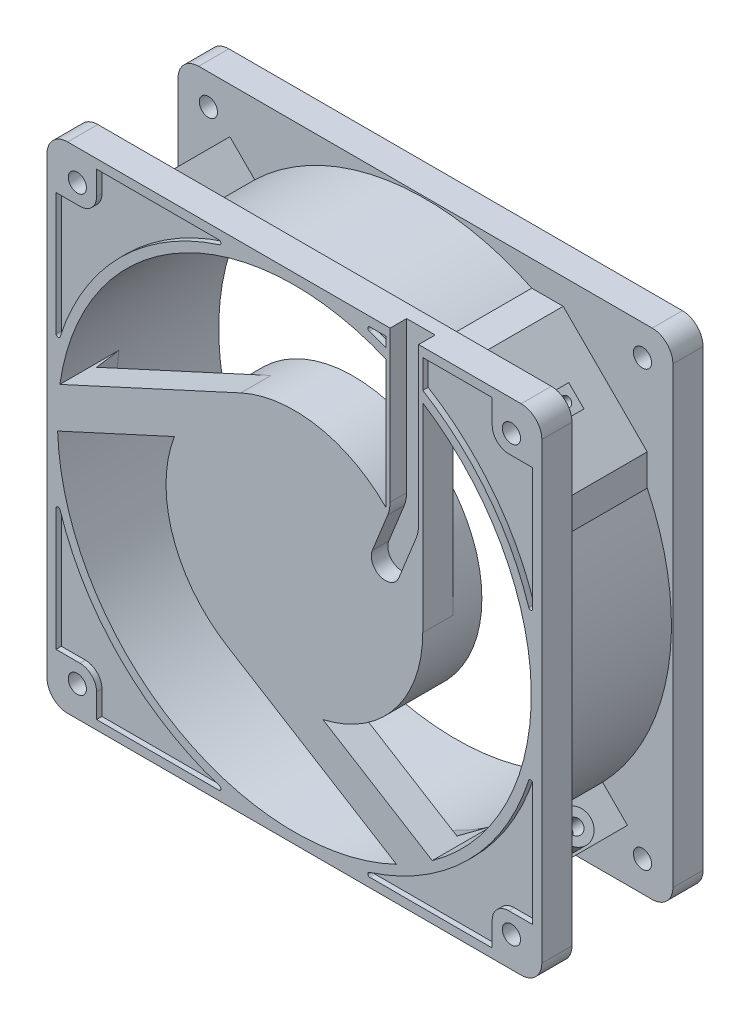
SolidWorks part; units mm, degrees
ref_plane "Plane1" through (0, 0, 0) normal (0, 0, 1) x (1, 0, 0)
ref_plane "Plane2" through (0, 0, 0) normal (0, 1, 0) x (1, 0, 0)
ref_plane "Plane3" through (0, 0, 0) normal (1, 0, 0) x (0, 0, -1)
sketch "Sketch1" plane through (0, 0, 0) normal (0, 0, 1) x (1, 0, 0)
  line L1 (-54.85, 59.85) -> (54.85, 59.85)
  line L2 (-59.85, 54.85) -> (-59.85, -54.85)
  line L3 (-54.85, -59.85) -> (54.85, -59.85)
  line L4 (59.85, 54.85) -> (59.85, -54.85)
  circle A0 centre (-52.5, 52.5) radius 2.2
  circle A1 centre (52.5, 52.5) radius 2.2
  circle A2 centre (52.5, -52.5) radius 2.2
  circle A3 centre (-52.5, -52.5) radius 2.2
  circle A4 centre (0, 0) radius 57.3
  arc A5 (59.85, 54.85) -> (54.85, 59.85) centre (54.85, 54.85) ccw
  arc A6 (59.85, -54.85) -> (54.85, -59.85) centre (54.85, -54.85) cw
  arc A7 (-54.85, -59.85) -> (-59.85, -54.85) centre (-54.85, -54.85) cw
  arc A8 (-59.85, 54.85) -> (-54.85, 59.85) centre (-54.85, 54.85) cw
  dimension "D3" = 4.4
  dimension "D5" = 114.6
  dimension "D6" = 5
  dimension "D11" = 105
  dimension "D1" = 119.7
  dimension "D2" = 119.7
  dimension "D4" = 7.35
  dimension "D7" = 59.85
  dimension "D8" = 59.85
  dimension "D9" = 105
  dimension "D10" = 7.35
extrude "Base-Extrude" add sketch "Sketch1" along normal mid plane 39
sketch "Sketch2" plane through (0, 0, 19.5) normal (0, 0, 1) x (1, 0, 0)
  line L34 (-18.2723, 57.65) -> (-47.85, 57.65)
  line L35 (57.65, 18.2723) -> (57.65, 47.85)
  line L36 (18.2723, -57.65) -> (47.85, -57.65)
  line L37 (-57.65, -18.2723) -> (-57.65, -47.85)
  line L38 (-57.65, 54.85) -> (-57.65, -54.85)
  line L39 (54.85, 57.65) -> (-54.85, 57.65)
  line L40 (57.65, -54.85) -> (57.65, 54.85)
  line L41 (-54.85, -57.65) -> (54.85, -57.65)
  line L42 (-57.65, 47.85) -> (-57.65, 18.2723)
  line L43 (47.85, 57.65) -> (18.2723, 57.65)
  line L44 (57.65, -47.85) -> (57.65, -18.2723)
  line L45 (-47.85, -57.65) -> (-18.2723, -57.65)
  line L55 (47.85, 57.65) -> (47.85, 51.85)
  line L56 (51.85, 47.85) -> (57.65, 47.85)
  line L57 (51.85, -47.85) -> (57.65, -47.85)
  line L58 (47.85, -51.85) -> (47.85, -57.65)
  line L59 (-57.65, -47.85) -> (-51.85, -47.85)
  line L60 (-47.85, -51.85) -> (-47.85, -57.65)
  line L61 (-57.65, 47.85) -> (-51.85, 47.85)
  line L62 (-47.85, 51.85) -> (-47.85, 57.65)
  arc A10 (47.85, -51.85) -> (51.85, -47.85) centre (51.85, -51.85) cw
  arc A11 (51.85, 47.85) -> (47.85, 51.85) centre (51.85, 51.85) cw
  arc A12 (-47.85, 51.85) -> (-51.85, 47.85) centre (-51.85, 51.85) cw
  arc A13 (-47.85, -51.85) -> (-51.85, -47.85) centre (-51.85, -51.85) ccw
  arc A14 (-18.2723, -57.65) -> (-18.12, -56.6737) centre (-18.2723, -57.15) ccw
  arc A15 (-57.65, -18.2723) -> (-56.6738, -18.12) centre (-57.15, -18.2723) cw
  arc A16 (18.2723, -57.65) -> (18.12, -56.6737) centre (18.2723, -57.15) cw
  arc A17 (56.6737, 18.12) -> (18.12, 56.6737) centre (0, 0) ccw
  circle A18 centre (0, 0) radius 59.5
  arc A19 (-18.12, 56.6737) -> (-56.6738, 18.12) centre (0, 0) ccw
  arc A20 (-57.65, -54.85) -> (-54.85, -57.65) centre (-54.85, -54.85) ccw
  arc A21 (-54.85, 57.65) -> (-57.65, 54.85) centre (-54.85, 54.85) ccw
  arc A22 (57.65, 54.85) -> (54.85, 57.65) centre (54.85, 54.85) ccw
  arc A23 (54.85, -57.65) -> (57.65, -54.85) centre (54.85, -54.85) ccw
  arc A24 (57.65, -18.2723) -> (56.6737, -18.12) centre (57.15, -18.2723) ccw
  arc A25 (57.65, 18.2723) -> (56.6737, 18.12) centre (57.15, 18.2723) cw
  arc A26 (18.2723, 57.65) -> (18.12, 56.6737) centre (18.2723, 57.15) ccw
  arc A27 (-18.2723, 57.65) -> (-18.12, 56.6737) centre (-18.2723, 57.15) cw
  arc A28 (18.12, -56.6737) -> (56.6737, -18.12) centre (0, 0) ccw
  arc A29 (-56.6738, -18.12) -> (-18.12, -56.6737) centre (0, 0) ccw
  arc A30 (-57.65, 18.2723) -> (-56.6738, 18.12) centre (-57.15, 18.2723) ccw
  point P54 (-57.65, -14.7217)
  point P57 (14.7217, -57.65)
  point P62 (57.65, 14.7217)
  point P67 (-14.7217, 57.65)
  dimension "D7" = 4
  dimension "D8" = 0.5
  dimension "D3" = 47.85
  dimension "D5" = 47.85
  dimension "D9" = 47.85
  dimension "D10" = 4
  dimension "D4" = 51.85
  dimension "D6" = 47.85
  dimension "D12" = 47.85
  dimension "D13" = 4
  dimension "D11" = 47.85
  dimension "D1" = 2.2
  dimension "D2" = 2.2
extrude "Cut-Extrude2" cut sketch "Sketch2" against normal blind 1.3
mirror "Mirror1" about plane through (0, 0, 0) normal (0, 0, 1) of "Cut-Extrude2"
sketch "Sketch3" plane through (0, 0, 0) normal (0, 0, 1) x (1, 0, 0)
  line L0 (-48.8611, 47.3054) -> (-47.3054, 48.8611)
  line L2 (54.85, 59.85) -> (-54.85, 59.85) construction
  line L3 (47.3054, -48.8611) -> (48.8611, -47.3054)
  line L4 (42.8435, -41.2878) -> (48.8611, -47.3054)
  line L5 (-48.8611, 47.3054) -> (-42.8435, 41.2878)
  line L6 (-48.8611, -47.3054) -> (-47.3054, -48.8611)
  line L7 (-47.3054, 48.8611) -> (-41.2878, 42.8435)
  line L8 (-48.8611, -47.3054) -> (-42.8435, -41.2878)
  line L9 (-47.3054, -48.8611) -> (-41.2878, -42.8435)
  line L10 (41.2878, -42.8435) -> (47.3054, -48.8611)
  line L11 (-59.85, 54.85) -> (-59.85, -54.85) construction
  line L12 (-54.85, -59.85) -> (54.85, -59.85) construction
  line L14 (33.3241, 53.65) -> (53.65, 33.3241)
  line L17 (47.85, 53.65) -> (18.2723, 53.65)
  line L18 (33.3241, 53.65) -> (25.728, 53.65)
  line L19 (59.85, -54.85) -> (59.85, 54.85) construction
  line L20 (53.65, 18.2723) -> (53.65, 47.85)
  line L21 (53.65, 25.728) -> (53.65, 33.3241)
  line L22 (-59.85, 54.85) -> (-59.85, -54.85)
  line L23 (-54.85, -59.85) -> (54.85, -59.85)
  line L24 (59.85, -54.85) -> (59.85, 54.85)
  line L25 (54.85, 59.85) -> (-54.85, 59.85)
  arc A0 (56.6737, 18.12) -> (18.12, 56.6737) centre (0, 0) ccw construction
  arc A1 (56.6737, -18.12) -> (53.65, 25.728) centre (0, 0) ccw
  arc A2 (18.12, -56.6737) -> (56.6737, -18.12) centre (0, 0) ccw construction
  arc A3 (-41.2878, -42.8435) -> (18.12, -56.6737) centre (0, 0) ccw
  arc A4 (-42.8435, 41.2878) -> (-42.8435, -41.2878) centre (0, 0) ccw
  arc A5 (18.12, -56.6737) -> (41.2878, -42.8435) centre (0, 0) ccw
  arc A6 (42.8435, -41.2878) -> (56.6737, -18.12) centre (0, 0) ccw
  arc A7 (25.728, 53.65) -> (-41.2878, 42.8435) centre (0, 0) ccw
  arc A9 (-59.85, -54.85) -> (-54.85, -59.85) centre (-54.85, -54.85) ccw construction
  arc A10 (54.85, -59.85) -> (59.85, -54.85) centre (54.85, -54.85) ccw construction
  arc A12 (59.85, 54.85) -> (54.85, 59.85) centre (54.85, 54.85) ccw construction
  arc A13 (-59.85, -54.85) -> (-54.85, -59.85) centre (-54.85, -54.85) ccw
  arc A14 (54.85, -59.85) -> (59.85, -54.85) centre (54.85, -54.85) ccw
  arc A15 (59.85, 54.85) -> (54.85, 59.85) centre (54.85, 54.85) ccw
  arc A16 (-54.85, 59.85) -> (-59.85, 54.85) centre (-54.85, 54.85) ccw construction
  arc A17 (-54.85, 59.85) -> (-59.85, 54.85) centre (-54.85, 54.85) ccw
  dimension "D1" = 10.9889
  dimension "D7" = 12.5446
  dimension "D6" = 1.5556
  dimension "D2" = 12.5446
  dimension "D3" = 12.5446
  dimension "D4" = 10.9889
  dimension "D5" = 107.1554
  dimension "D8" = 10.9889
  dimension "D9" = 107.1554
  dimension "D10" = 1.5556
  dimension "D11" = 12.5446
  dimension "D12" = 1.1
  dimension "D13" = 1.1
  dimension "D14" = 2.2
  dimension "D15" = 61.5
  dimension "D16" = 4
  dimension "D17" = 4
extrude "Cut-Extrude3" cut sketch "Sketch3" against normal mid plane 24.4
sketch "Sketch4" plane through (62.5613, 24.4129, 0) normal (-0.7071, -0.7071, 0) x (0.7071, -0.7071, 0)
  line L1 (-24.375, 2.6) -> (-29.575, 2.6)
  line L2 (-24.375, 2.6) -> (-24.375, -2.6)
  line L3 (-24.375, -2.6) -> (-29.575, -2.6)
  line L4 (-29.575, 2.6) -> (-29.575, -2.6)
  circle A0 centre (-26.975, 0) radius 1.2
  dimension "D5" = 2.4
  dimension "D1" = 5.2
  dimension "D2" = 5.2
  dimension "D3" = 2.6
  dimension "D4" = 2.6
extrude "Boss-Extrude2" add sketch "Sketch4" against normal blind 3.7
sketch "Sketch5" plane through (0.7778, 0.7778, 0) normal (0.7071, 0.7071, 0) x (-0.7071, 0.7071, 0)
  line L0 (-59.4898, -12.2) -> (-59.4898, 12.2) construction
  circle A0 centre (-63.7398, 0) radius 3.7
  circle A1 centre (-63.7398, 0) radius 1.7
  dimension "D1" = 7.4
  dimension "D3" = 3.4
  dimension "D2" = 4.25
extrude "Boss-Extrude3" add sketch "Sketch5" along normal blind 3.7
sketch "Sketch6" plane through (0, 0, 19.5) normal (0, 0, 1) x (1, 0, 0)
  line L0 (31.05, 59.85) -> (31.05, 0)
  line L1 (22.15, 59.85) -> (22.15, 21.7596)
  line L2 (54.85, 59.85) -> (-54.85, 59.85) construction
  line L3 (31.05, 59.85) -> (22.15, 59.85)
  line L4 (6.8925, -30.2753) -> (33.3508, -46.5941)
  line L5 (-12.9578, 28.217) -> (-56.7218, 8.1197)
  line L6 (-29.0179, 11.0483) -> (-57.2677, -1.9246)
  line L7 (-16.2999, -26.4276) -> (24.6888, -51.7083)
  line L8 (-18.2723, 57.65) -> (-47.85, 57.65) construction
  line L9 (-54.85, -59.85) -> (54.85, -59.85) construction
  arc A0 (22.15, 21.7596) -> (-12.9578, 28.217) centre (0, 0) ccw
  circle A1 centre (0, 0) radius 57.3 construction
  arc A2 (-56.7218, 8.1197) -> (-57.2677, -1.9246) centre (0, 0) ccw
  arc A3 (-29.0179, 11.0483) -> (-16.2999, -26.4276) centre (0, 0) ccw
  arc A4 (24.6888, -51.7083) -> (33.3508, -46.5941) centre (0, 0) ccw
  arc A5 (6.8925, -30.2753) -> (31.05, 0) centre (0, 0) ccw
  dimension "D1" = 62.1
  dimension "D3" = 49.5303
  dimension "D4" = 61.7746
  dimension "D5" = 13.2559
  dimension "D6" = 8.1417
  dimension "D7" = 28.2498
  dimension "D8" = 16.3188
  dimension "D2" = 8.9
extrude "Boss-Extrude4" add sketch "Sketch6" against normal blind 14.3
sketch "Sketch8" plane through (0, 0, 5.2) normal (0, 0, -1) x (-1, 0, 0)
  line L4 (-22.15, 55.2234) -> (-22.15, 59.85)
  line L5 (-22.15, 59.85) -> (-31.05, 59.85)
  line L6 (-31.05, 59.85) -> (-31.05, 53.65)
  line L7 (-31.05, 53.65) -> (-25.728, 53.65)
  line L8 (-22.15, 55.2234) -> (-22.15, 59.85)
  line L9 (-22.15, 59.85) -> (-31.05, 59.85)
  line L10 (-31.05, 59.85) -> (-31.05, 53.65)
  line L11 (-31.05, 53.65) -> (-25.728, 53.65)
  arc A1 (-22.15, 55.2234) -> (-25.728, 53.65) centre (0, 0) ccw
  arc A2 (-22.15, 55.2234) -> (-25.728, 53.65) centre (0, 0) ccw
  dimension "D1" = 0
extrude "Cut-Extrude6" cut sketch "Sketch8" against normal up to surface (7 mm away)
sketch "Sketch9" plane through (0, 0, 0) normal (1, 0, 0) x (0, 0, -1)
  line L0 (-12.2, 55.85) -> (-5.2, 57.3)
  line L1 (12.2, 59.5) -> (-12.2, 59.5) construction
  line L3 (-5.2, 52.8457) -> (-5.2, 21.7596) construction
  line L4 (-5.2, 57.3) -> (-5.2, 31.05)
  line L5 (-5.2, 31.05) -> (-19.5, 31.05) construction
  line L6 (-5.2, 31.05) -> (-12.2, 31.05)
  line L7 (-12.2, 55.85) -> (-12.2, 31.05)
  line L8 (-26.3288, 0) -> (30.8074, 0) construction
  line L9 (-18.2, 0) -> (-19.5, 0) construction
  dimension "D1" = 7
  dimension "D2" = 1.45
  dimension "D3" = 2.2
revolve "Cut-Revolve1" cut sketch "Sketch9" angle 360 about L8
sketch "Sketch10" plane through (0, 0, 5.2) normal (0, 0, -1) x (-1, 0, 0)
  circle A0 centre (0, 0) radius 4.5
  dimension "D1" = 9
extrude "Boss-Extrude5" add sketch "Sketch10" along normal blind 7
sketch "Sketch11" plane through (0, 0, 19.5) normal (0, 0, 1) x (1, 0, 0)
  line L4 (30.05, 22.0376) -> (30.05, 59.85)
  line L5 (54.85, 59.85) -> (-54.85, 59.85) construction
  line L6 (23.15, 52.8457) -> (23.15, 21.7596)
  line L7 (23.15, 59.85) -> (23.15, 23.3739)
  line L8 (30.05, 59.85) -> (23.15, 59.85)
  line L9 (22.5716, 20.3872) -> (18.8494, 11.138)
  line L10 (25.2506, 8.562) -> (29.4716, 19.0509)
  arc A0 (18.8494, 11.138) -> (25.2506, 8.562) centre (22.05, 9.85) ccw
  arc A1 (23.15, 23.3739) -> (22.5716, 20.3872) centre (15.15, 23.3739) cw
  arc A2 (30.05, 22.0376) -> (29.4716, 19.0509) centre (22.05, 22.0376) cw
  dimension "D3" = 6.9
  dimension "D4" = 6.9
  dimension "D5" = 8
  dimension "D6" = 50
  dimension "D1" = 8
  dimension "D7" = 37.8124
  dimension "D2" = 1
extrude "Cut-Extrude7" cut sketch "Sketch11" against normal blind 4
